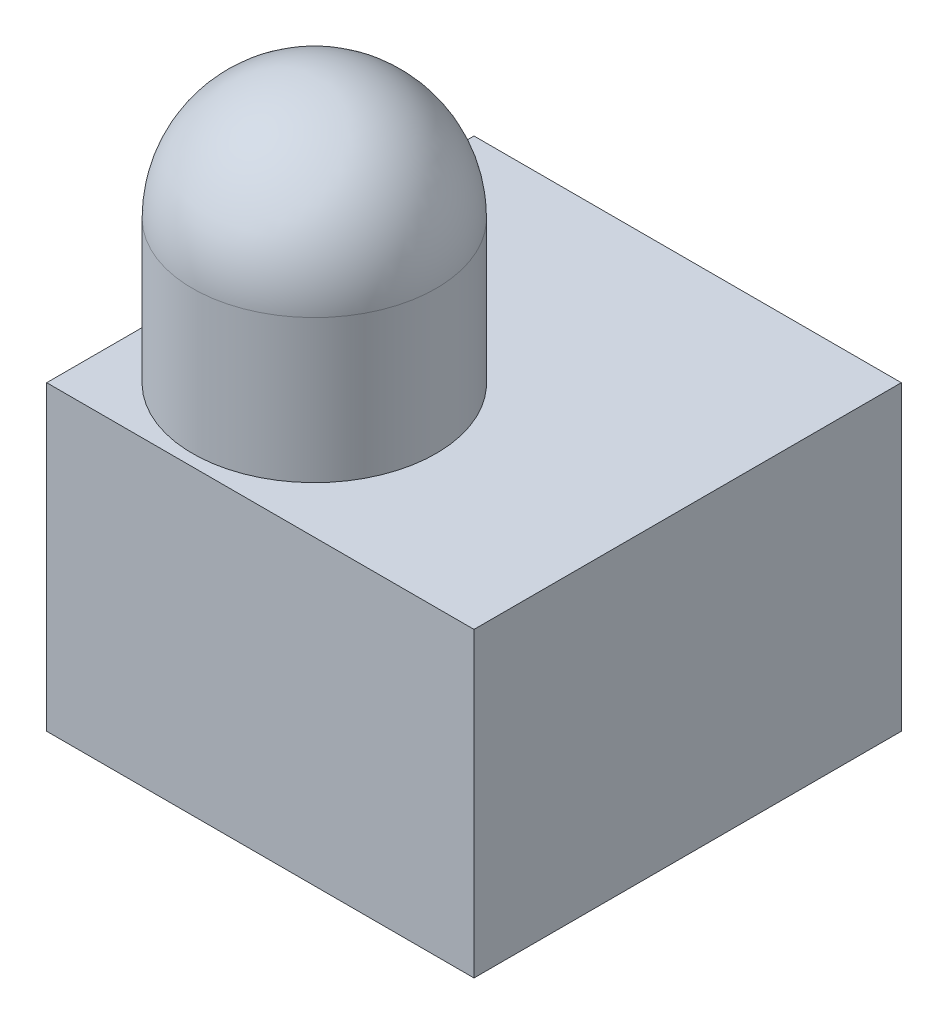
SolidWorks part; units mm, degrees
ref_plane "Front Plane" through (0, 0, 0) normal (0, 0, 1) x (1, 0, 0)
ref_plane "Top Plane" through (0, 0, 0) normal (0, 1, 0) x (1, 0, 0)
ref_plane "Right Plane" through (0, 0, 0) normal (1, 0, 0) x (0, 0, -1)
sketch "Sketch1" plane through (0, 0, 0) normal (0, 1, 0) x (1, 0, 0)
  line L1 (116.84, -116.84) -> (-116.84, -116.84)
  line L2 (116.84, -116.84) -> (116.84, 116.84)
  line L3 (116.84, 116.84) -> (-116.84, 116.84)
  line L4 (-116.84, -116.84) -> (-116.84, 116.84)
  line L5 (116.84, -116.84) -> (-116.84, 116.84) construction
  line L6 (116.84, 116.84) -> (-116.84, -116.84) construction
  point P0 (0, 0)
  dimension "D1" = 233.68
  dimension "D2" = 233.68
extrude "Boss-Extrude1" add sketch "Sketch1" along normal blind 165.1
sketch "Sketch2" plane through (0, 165.1, 0) normal (0, 1, 0) x (1, 0, 0)
  point P0 (-43.4095, -43.917)
ref_axis "Axis1" through (-43.4095, 165.1, 43.917) along (0, 1, 0)
ref_plane "Plane1" through (-43.4095, 0, 0) normal (1, 0, 0) x (0, 1, 0)
sketch "Sketch3" plane through (-43.4095, 0, 0) normal (1, 0, 0) x (0, 1, 0)
  line L0 (165.1, 43.917) -> (309.8835, 43.917)
  line L1 (165.1, 43.917) -> (274.1562, 43.917) construction
  line L2 (243.2692, -22.6972) -> (165.1, -22.6972)
  line L3 (165.1, 116.84) -> (165.1, -116.84) construction
  line L5 (165.1, -22.6972) -> (165.1, 43.917)
  arc A0 (243.2692, -22.6972) -> (309.8835, 43.917) centre (243.2692, 43.917) ccw
  point P7 (288.5131, 43.917)
  point P8 (243.2692, -22.6972)
revolve "Revolve1" add sketch "Sketch3" angle 360 about axis through (-43.4095, 165.1, 43.917) along (0, 1, 0)
